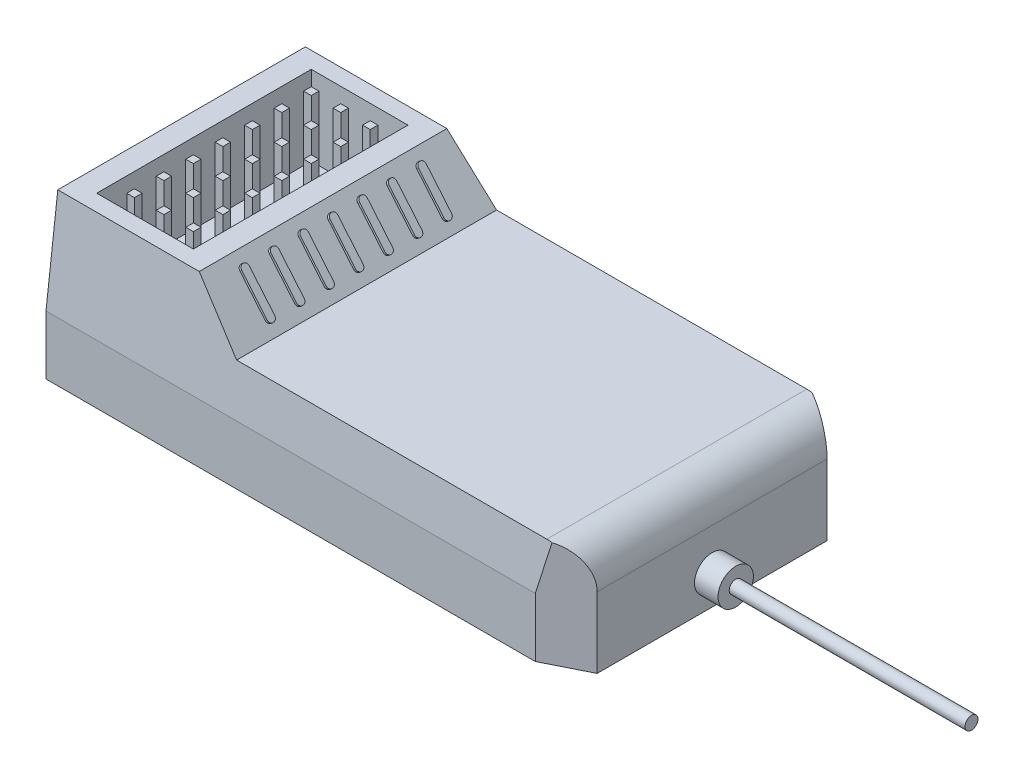
SolidWorks part; units mm, degrees
ref_plane "Plan de face" through (0, 0, 0) normal (0, 0, 1) x (1, 0, 0)
ref_plane "Plan de dessus" through (0, 0, 0) normal (0, 1, 0) x (1, 0, 0)
ref_plane "Plan de droite" through (0, 0, 0) normal (1, 0, 0) x (0, 0, -1)
sketch "Esquisse1" plane through (0, 0, 0) normal (0, 1, 0) x (1, 0, 0)
  line L0 (-22.5, 11.5) -> (22.5, -11.5) construction
  line L1 (-22.5, 11.5) -> (22.5, 11.5)
  line L2 (-22.5, 11.5) -> (-22.5, -11.5)
  line L3 (-22.5, -11.5) -> (22.5, -11.5)
  line L4 (22.5, 11.5) -> (22.5, -11.5)
  dimension "D1" = 45
  dimension "D2" = 23
extrude "Extrusion1" add sketch "Esquisse1" along normal blind 13.4
sketch "Esquisse2" plane through (0, 0, 0) normal (0, 0, 1) x (1, 0, 0)
  line L0 (22.5, 13.4) -> (22.5, 0) construction
  line L1 (-22.5, 13.4) -> (22.5, 13.4) construction
  line L3 (22.5, 13.4) -> (22.5, 9)
  line L5 (-10.5, 13.4) -> (22.5, 13.4)
  line L6 (-22.5, 0) -> (22.5, 0) construction
  line L8 (-22.5, 13.4) -> (-22.5, 0) construction
  line L9 (22.5, 9) -> (-6.808, 9)
  line L10 (-6.808, 9) -> (-10.5, 13.4)
  dimension "D1" = 9
  dimension "D2" = 12
  dimension "D3" = 40
extrude "Enlèv. mat.-Extru.1" cut sketch "Esquisse2" against normal through all and the other way through all
sketch "Esquisse3" plane through (0, 0, 0) normal (1, 0, 0) x (0, 0, -1)
  line L0 (-10.5, 13.4) -> (-11.5, 5)
  line L1 (11.5, 13.4) -> (-11.5, 13.4) construction
  line L2 (-11.5, 9) -> (-11.5, 0) construction
  line L3 (-10.5, 13.4) -> (10.5, 13.4)
  line L4 (11.5, 13.4) -> (-11.5, 13.4) construction
  line L5 (10.5, 13.4) -> (11.5, 5)
  line L6 (11.5, 13.4) -> (11.5, 0) construction
  line L7 (11.5, 0) -> (-11.5, 0) construction
  dimension "D1" = 21
  dimension "D2" = 5
extrude "Enlèv. mat.-Extru.2" cut sketch "Esquisse3" against normal through all and the other way through all
fillet "Congé1" radius 3 1 edges at (22.5, 9, 0)
sketch "Esquisse4" plane through (0, 0, 0) normal (0, 1, 0) x (1, 0, 0)
  line L0 (22.5, -11.5) -> (22.5, 11.5) construction
  line L1 (22.5, 11.5) -> (-22.5, 11.5) construction
  line L2 (-22.5, -11.5) -> (22.5, -11.5) construction
  line L3 (22.5, -11.5) -> (22.5, 11.5) construction
  line L4 (22.5, 11.5) -> (19, 11.5)
  line L5 (19, -11.5) -> (22.5, -11.5)
  line L6 (19, 11.5) -> (42, 0)
  line L7 (42, 0) -> (19, -11.5)
  point P4 (22.5, 9.75)
  point P9 (22.5, -9.75)
  dimension "D1" = 3.5
  dimension "D2" = 19.5
extrude "Enlèv. mat.-Extru.3" cut sketch "Esquisse4" against normal through all and the other way through all
sketch "Esquisse5" plane through (0, 13.4, 0) normal (0, 1, 0) x (-1, 0, 0)
  line L0 (12.4, 0) -> (10.5, 0) construction
  line L1 (20.6, -9.1) -> (12.4, -9.1)
  line L2 (20.6, -9.1) -> (20.6, 9.1)
  line L3 (20.6, 9.1) -> (12.4, 9.1)
  line L4 (12.4, -9.1) -> (12.4, 9.1)
  line L5 (10.5, -10.5) -> (10.5, 10.5) construction
  line L6 (20.6, 0) -> (22.5, 0) construction
  line L7 (22.5, -10.5) -> (22.5, 10.5) construction
  dimension "D1" = 8.2
  dimension "D2" = 18.2
extrude "Enlèv. mat.-Extru.4" cut sketch "Esquisse5" against normal blind 6.75
sketch "Esquisse6" plane through (22.5, 0, 0) normal (1, 0, 0) x (0, 0, -1)
  line L0 (-9.75, 0) -> (9.75, 0) construction
  circle A0 centre (0, 2.5) radius 1.5
  dimension "D1" = 3
  dimension "D2" = 2.5
extrude "Extrusion2" add sketch "Esquisse6" along normal blind 2
sketch "Esquisse7" plane through (24.5, 0, 0) normal (1, 0, 0) x (0, 0, -1)
  circle A0 centre (0, 2.5) radius 0.55
  dimension "D1" = 1.1
extrude "Extrusion3" add sketch "Esquisse7" along normal blind 20
sketch "Esquisse8" plane through (0, 13.4, 0) normal (0, 1, 0) x (-1, 0, 0)
  line L0 (12.4, -9.1) -> (20.6, -9.1) construction
  line L1 (13.675, -7.825) -> (14.325, -7.825)
  line L2 (13.675, -7.825) -> (13.675, -7.175)
  line L3 (13.675, -7.175) -> (14.325, -7.175)
  line L4 (14.325, -7.825) -> (14.325, -7.175)
  line L5 (13.675, -7.5) -> (12.4, -7.5) construction
  line L6 (12.4, 9.1) -> (12.4, -9.1) construction
  line L7 (14, -7.825) -> (14, -9.1) construction
  line L8 (12.4, -9.1) -> (20.6, -9.1) construction
  dimension "D1" = 0.65
  dimension "D2" = 1.275
extrude "Extrusion4" add sketch "Esquisse8" against normal up to next
pattern_linear "Répétition linéaire1" count 3 spacing 2.5 along (-1, 0, 0) count 7 spacing 2.5 along (0, 0, 1) of "Extrusion4"
sketch "Esquisse9" plane through (0.4366, 0.3663, 0) normal (0.766, 0.6428, 0) x (0, 0, -1)
  line L11 (7.5, 15.8174) -> (7.5, 17.0143) construction
  line L12 (10.5, 17.0143) -> (-10.5, 17.0143) construction
  line L15 (7.5, 12.4674) -> (7.5, 11.2705) construction
  line L16 (7.175, 13.8843) -> (7.175, 19.0551) construction
  line L17 (7.825, 13.8843) -> (7.825, 19.0551) construction
  line L22 (7.175, 12.4674) -> (7.175, 15.8174)
  line L23 (7.825, 12.4674) -> (7.825, 15.8174)
  line L24 (11.0238, 11.2705) -> (-11.0238, 11.2705) construction
  arc A0 (7.175, 15.8174) -> (7.825, 15.8174) centre (7.5, 15.8174) cw
  arc A1 (7.175, 12.4674) -> (7.825, 12.4674) centre (7.5, 12.4674) ccw
  dimension "D1" = 4
extrude "Extrusion5" add sketch "Esquisse9" along normal blind 0.2
pattern_linear "Répétition linéaire2" count 7 spacing 2.5 along (0, 0, 1) of "Extrusion5"
